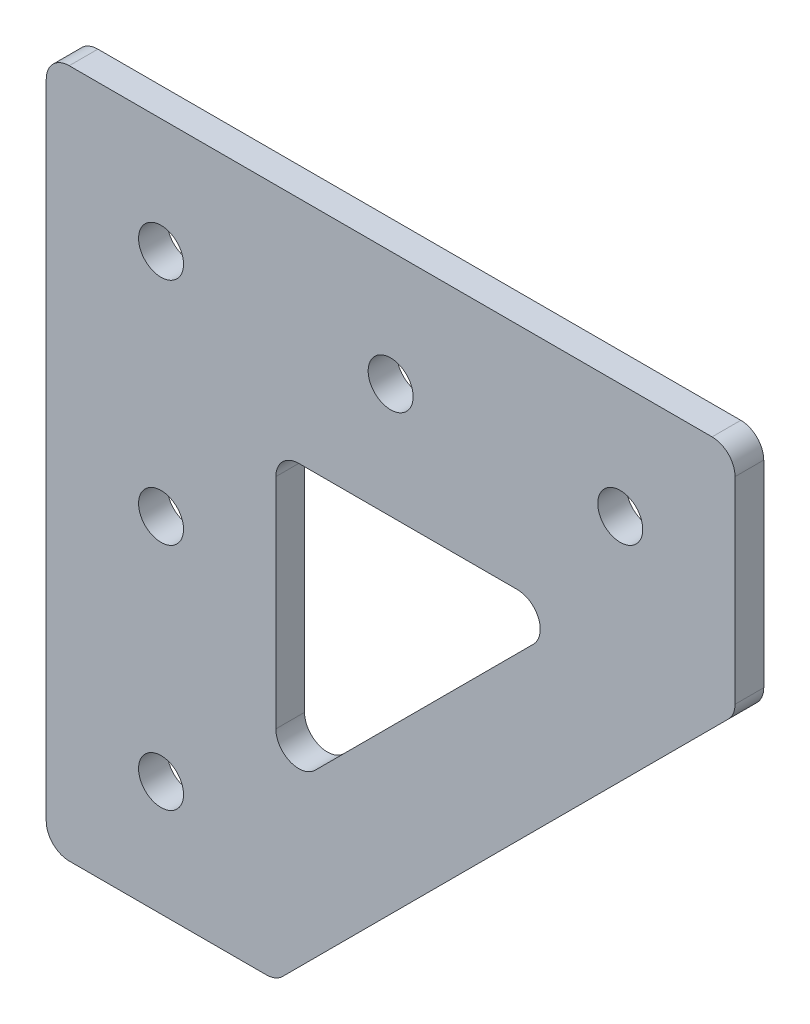
SolidWorks part; units mm, degrees
material "6061-T6 (SS)"
ref_plane "Front Plane" through (0, 0, 0) normal (0, 0, 1) x (1, 0, 0)
ref_plane "Top Plane" through (0, 0, 0) normal (0, 1, 0) x (1, 0, 0)
ref_plane "Right Plane" through (0, 0, 0) normal (1, 0, 0) x (0, 0, -1)
sketch "Sketch1" plane through (0, 0, 0) normal (0, 0, 1) x (1, 0, 0)
  line L0 (0, 0) -> (0, 76.2)
  line L9 (0, 76.2) -> (76.2, 76.2)
  line L10 (76.2, 76.2) -> (76.2, 50.8)
  line L11 (58.2395, 50.8) -> (25.4, 50.8)
  line L12 (25.4, 50.8) -> (25.4, 17.9605)
  line L13 (25.4, 0) -> (0, 0)
  line L14 (25.4, 0) -> (76.2, 50.8)
  line L15 (58.2395, 50.8) -> (25.4, 17.9605)
  dimension "D1" = 25.4
  dimension "D2" = 25.4
  dimension "D3" = 76.2
  dimension "D4" = 76.2
  dimension "D5" = 12.7
extrude "Boss-Extrude1" add sketch "Sketch1" against normal blind 3.175 contours L13 L14 L10 L9 L0 L11 L15 L12
sketch "Sketch2" plane through (0, 0, 0) normal (0, 0, 1) x (1, 0, 0)
  line L0 (0, 76.2) -> (76.2, 76.2) construction
  line L1 (0, 0) -> (0, 76.2) construction
  circle A0 centre (12.7, 63.5) radius 2.4892
  circle A1 centre (38.1, 63.5) radius 2.4892
  circle A2 centre (63.5, 63.5) radius 2.4892
  circle A3 centre (12.7, 38.1) radius 2.4892
  circle A4 centre (12.7, 12.7) radius 2.4892
  dimension "D3" = 4.9784
  dimension "D1" = 12.7
  dimension "D2" = 12.7
  dimension "D4" = 3
  dimension "D5" = 3
extrude "Cut-Extrude1" cut sketch "Sketch2" against normal through all
fillet "Fillet3" radius 2.54 8 edges at (58.2395, 50.8, -1.5875) (25.4, 17.9605, -1.5875) (25.4, 50.8, -1.5875) (25.4, 0, -1.5875) (76.2, 50.8, -1.5875) (76.2, 76.2, -1.5875) (0, 0, -1.5875) (0, 76.2, -1.5875)
